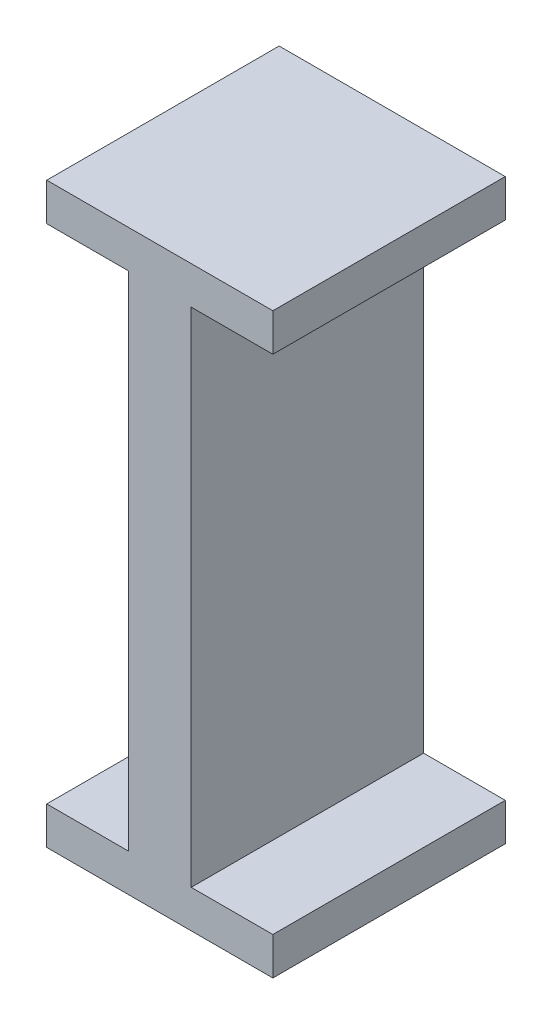
SolidWorks part; units mm, degrees
material "AISI 1010 钢，热轧条材"
ref_plane "前视基准面" through (0, 0, 0) normal (0, 0, 1) x (1, 0, 0)
ref_plane "上视基准面" through (0, 0, 0) normal (0, 1, 0) x (1, 0, 0)
ref_plane "右视基准面" through (0, 0, 0) normal (1, 0, 0) x (0, 0, -1)
sketch "草图1" plane through (0, 0, 0) normal (0, 1, 0) x (1, 0, 0)
  line L1 (-18, -18.5) -> (18, -18.5)
  line L2 (-18, -18.5) -> (-18, 18.5)
  line L3 (-18, 18.5) -> (18, 18.5)
  line L4 (18, -18.5) -> (18, 18.5)
  line L5 (-18, -18.5) -> (18, 18.5) construction
  line L6 (-18, 18.5) -> (18, -18.5) construction
  point P0 (0, 0)
  dimension "D1" = 37
  dimension "D2" = 36
extrude "凸台-拉伸1" add sketch "草图1" along normal blind 6
sketch "草图2" plane through (0, 6, 0) normal (0, 1, 0) x (1, 0, 0)
  line L0 (-18, -18.5) -> (18, -18.5) construction
  line L1 (5, 18.5) -> (-5, 18.5)
  line L2 (5, 18.5) -> (5, -18.5)
  line L3 (5, -18.5) -> (-5, -18.5)
  line L4 (-5, 18.5) -> (-5, -18.5)
  line L5 (5, 18.5) -> (-5, -18.5) construction
  line L6 (5, -18.5) -> (-5, 18.5) construction
  point P0 (0, 0)
  dimension "D1" = 10
extrude "凸台-拉伸2" add sketch "草图2" along normal blind 80
sketch "草图3" plane through (0, 86, 0) normal (0, 1, 0) x (1, 0, 0)
  line L1 (-18, 18.5) -> (18, 18.5)
  line L2 (-18, 18.5) -> (-18, -18.5)
  line L3 (-18, -18.5) -> (18, -18.5)
  line L4 (18, 18.5) -> (18, -18.5)
extrude "凸台-拉伸3" add sketch "草图3" along normal blind 6
